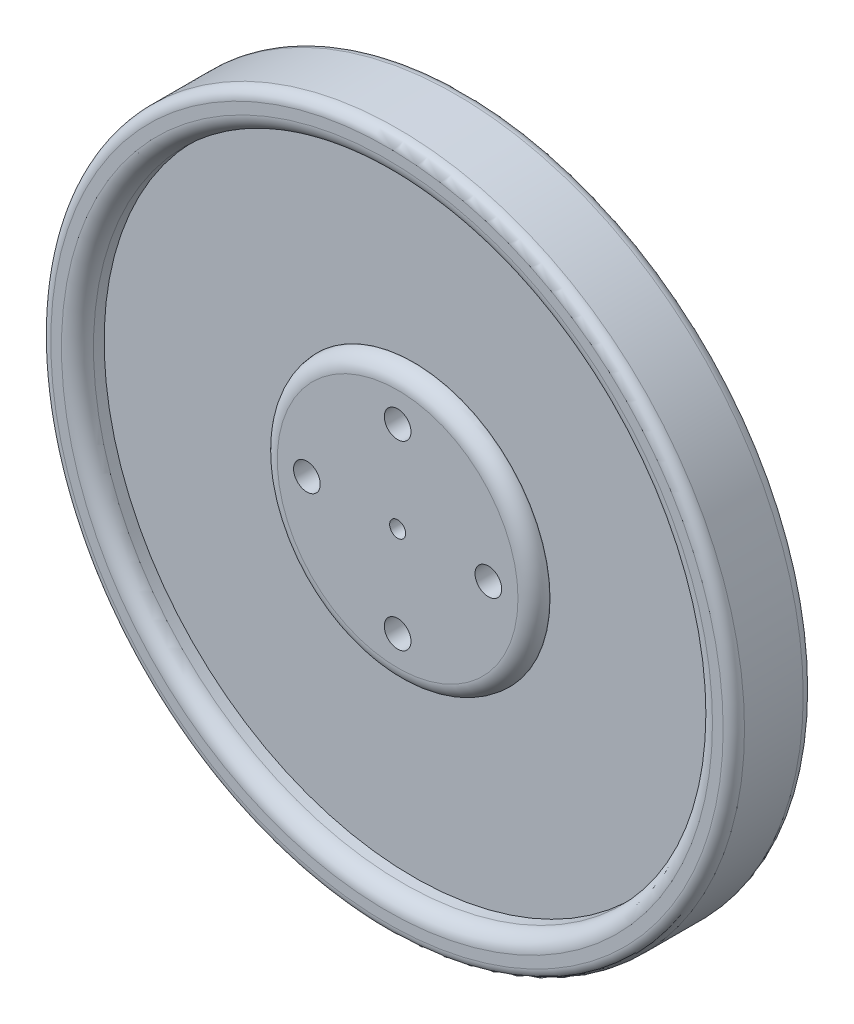
SolidWorks part; units mm, degrees
ref_plane "Plan de face" through (0, 0, 0) normal (0, 0, 1) x (1, 0, 0)
ref_plane "Plan de dessus" through (0, 0, 0) normal (0, 1, 0) x (1, 0, 0)
ref_plane "Plan de droite" through (0, 0, 0) normal (1, 0, 0) x (0, 0, -1)
sketch "Esquisse1" plane through (0, 0, 0) normal (0, 0, 1) x (1, 0, 0)
  circle A0 centre (0, 0) radius 32.5
extrude "Boss.-Extru.1" add sketch "Esquisse1" along normal blind 12
sketch "Esquisse2" plane through (0, 0, 12) normal (0, 0, 1) x (1, 0, 0)
  circle A0 centre (0, 0) radius 65
extrude "Enlèv. mat.-Extru.1" cut sketch "Esquisse2" against normal blind 3
sketch "Esquisse5" plane through (0, 0, 9) normal (0, 0, 1) x (1, 0, 0)
  circle A0 centre (0, 0) radius 29
extrude "Enlèv. mat.-Extru.4" cut sketch "Esquisse5" against normal blind 3
sketch "Esquisse6" plane through (0, 0, 6) normal (0, 0, 1) x (1, 0, 0)
  circle A0 centre (0, 0) radius 1
extrude "Enlèv. mat.-Extru.6" cut sketch "Esquisse6" against normal blind 32
sketch "Esquisse8" plane through (0, 0, 6) normal (0, 0, 1) x (1, 0, 0)
  line L0 (0, 0) -> (2.1808, 1.0719)
  line L1 (0, 0) -> (2.3, -0.7842)
  line L2 (0, 0) -> (1.0719, -2.1808)
  line L3 (0, 0) -> (-0.7842, -2.3)
  line L4 (0, 0) -> (-2.1808, -1.0719)
  line L5 (0, 0) -> (-2.3, 0.7842)
  line L6 (0, 0) -> (-1.0719, 2.1808)
  line L7 (0, 0) -> (0.7842, 2.3)
  line L8 (1.8667, 0.9175) -> (0, 0)
  line L9 (1.8667, 0.9175) -> (1.7125, 1.2313)
  line L10 (0, 0) -> (-0.1542, 0.3138)
  line L11 (1.7125, 1.2313) -> (-0.1542, 0.3138)
  line L12 (1.8667, 0.9175) -> (2.0211, 0.6034)
  line L13 (1.8667, 0.9175) -> (0.0147, 0.0072)
  line L14 (2.0211, 0.6034) -> (0.1691, -0.3069)
  line L15 (0.0147, 0.0072) -> (0.1691, -0.3069)
  line L16 (1.8558, -1.0025) -> (-0.0974, -0.3366)
  line L17 (2.0816, -0.3403) -> (0.1128, 0.331)
  line L18 (0.6034, -2.0211) -> (-0.3069, -0.1691)
  line L19 (1.2313, -1.7125) -> (0.3138, 0.1542)
  line L20 (-1.0025, -1.8558) -> (-0.3366, 0.0974)
  line L21 (-0.3403, -2.0816) -> (0.331, -0.1128)
  line L22 (-2.0211, -0.6034) -> (-0.1691, 0.3069)
  line L23 (-1.7125, -1.2313) -> (0.1542, -0.3138)
  line L24 (-1.8558, 1.0025) -> (0.0974, 0.3366)
  line L25 (-2.0816, 0.3403) -> (-0.1128, -0.331)
  line L26 (-0.6034, 2.0211) -> (0.3069, 0.1691)
  line L27 (-1.2313, 1.7125) -> (-0.3138, -0.1542)
  line L28 (1.0025, 1.8558) -> (0.3366, -0.0974)
  line L29 (0.3403, 2.0816) -> (-0.331, 0.1128)
  circle A0 centre (0, 0) radius 2.43
  circle A1 centre (1.8667, 0.9175) radius 0.35
  circle A2 centre (1.9687, -0.6712) radius 0.35
  circle A3 centre (0.9175, -1.8667) radius 0.35
  circle A4 centre (-0.6712, -1.9687) radius 0.35
  circle A5 centre (-1.8667, -0.9175) radius 0.35
  circle A6 centre (-1.9687, 0.6712) radius 0.35
  circle A7 centre (-0.9175, 1.8667) radius 0.35
  circle A8 centre (0.6712, 1.9687) radius 0.35
  point P14 (0, 0)
  point P63 (0, 0)
  dimension "D1" = 8
  dimension "D2" = 8
extrude "Enlèv. mat.-Extru.7" cut sketch "Esquisse8" against normal blind 32
sketch "Esquisse9" plane through (0, 0, 0) normal (0, 0, -1) x (-1, 0, 0)
  circle A0 centre (0, 0) radius 1.43
extrude "Enlèv. mat.-Extru.8" cut sketch "Esquisse9" against normal blind 32
sketch "Esquisse11" plane through (0, 0, 6) normal (0, 0, 1) x (1, 0, 0)
  circle A0 centre (0, 0) radius 2.43
extrude "Enlèv. mat.-Extru.9" cut sketch "Esquisse11" against normal blind 3
fillet "Congé7" radius 1 1 edges at (2.43, 0, 6)
sketch "Esquisse12" plane through (0, 0, 3) normal (0, 0, 1) x (1, 0, 0)
sketch "Esquisse14" plane through (0, 0, 6) normal (0, 0, 1) x (1, 0, 0)
  circle A0 centre (0, 0) radius 29
extrude "Enlèv. mat.-Extru.10" cut sketch "Esquisse14" against normal blind 1
sketch "Esquisse16" plane through (0, 0, 9) normal (0, 0, 1) x (1, 0, 0)
  circle A0 centre (0, 0) radius 39.3987
extrude "Enlèv. mat.-Extru.12" cut sketch "Esquisse16" against normal blind 1.5
sketch "Esquisse17" plane through (0, 0, 5) normal (0, 0, 1) x (1, 0, 0)
  circle A0 centre (0, 0) radius 29
fillet "Congé10" radius 1.5 1 edges at (29, 0, 7.5)
fillet "Congé11" radius 1 1 edges at (32.5, 0, 7.5)
fillet "Congé12" radius 1 1 edges at (32.5, 0, 0)
sketch "Esquisse18" plane through (0, 0, 0) normal (0, 0, -1) x (-1, 0, 0)
  line L0 (0, 0) -> (0, 29)
  line L1 (0, 29) -> (0, -29)
  line L2 (0, 0) -> (29, 0)
  line L3 (29, 0) -> (-29, 0)
  circle A0 centre (0, 0) radius 12.25
  circle A1 centre (0, 0) radius 8.5
  circle A2 centre (0, 0) radius 29 construction
  circle A3 centre (0, 8.5) radius 1.25
  circle A4 centre (0, -8.5) radius 1.25
  circle A5 centre (8.5, 0) radius 1.25
  circle A6 centre (-8.5, 0) radius 1.25
extrude "Enlèv. mat.-Extru.13" cut sketch "Esquisse18" against normal blind 10 contours A1 A3 L1 | L1 A3 A1 | L1 A3 A1 | A1 A3 L1 | L3 A6 A1 | A1 A6 L3 | L3 A6 A1 | A1 A6 L3 | A1 A5 L3 | L3 A5 A1 | A1 A5 L3 | L3 A5 A1 | A1 A4 L1 | L1 A4 A1 | A1 A4 L1 | L1 A4 A1
sketch "Esquisse19" plane through (0, 0, 0) normal (0, 0, -1) x (-1, 0, 0)
  circle A0 centre (0, 0) radius 3.3004
extrude "Boss.-Extru.2" add sketch "Esquisse19" against normal blind 5
sketch "Esquisse20" plane through (0, 0, 0) normal (0, 0, -1) x (-1, 0, 0)
  circle A0 centre (0, 0) radius 12.25
extrude "Enlèv. mat.-Extru.14" cut sketch "Esquisse20" against normal blind 3
sketch "Esquisse21" plane through (0, 0, 5) normal (0, 0, 1) x (1, 0, 0)
  circle A0 centre (0, 0) radius 12.75
extrude "Boss.-Extru.3" add sketch "Esquisse21" along normal blind 1.5
draft "Dépouille1" type of draft neutral plane draft angle 1 faces to draft 1 face at (12.75, 0, 6.5) neutral plane through (0, 0, 6.5) neutral plane normal (0, 0, 1) parameters "D1"=1
fillet "Congé13" radius 1.5 1 edges at (12.75, 0, 6.5)
sketch "Esquisse22" plane through (0, 0, 5) normal (0, 0, -1) x (-1, 0, 0)
  circle A0 centre (0, 8.5) radius 1.25
  circle A1 centre (-8.5, 0) radius 1.25
  circle A2 centre (8.5, 0) radius 1.25
  circle A3 centre (0, -8.5) radius 1.25
extrude "Enlèv. mat.-Extru.15" cut sketch "Esquisse22" against normal blind 1.5
sketch "Esquisse23" plane through (0, 0, 3) normal (0, 0, -1) x (-1, 0, 0)
  circle A0 centre (0, 0) radius 0.75
extrude "Enlèv. mat.-Extru.16" cut sketch "Esquisse23" against normal blind 12.5
